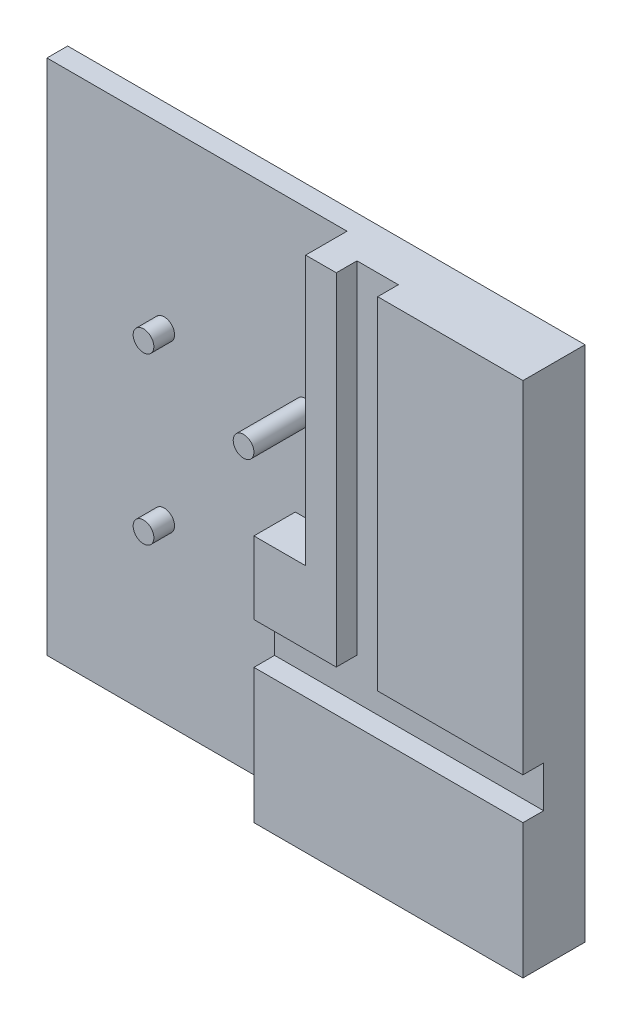
SolidWorks part; units mm, degrees
material "普通碳钢"
ref_plane "前视基准面" through (0, 0, 0) normal (0, 0, 1) x (1, 0, 0)
ref_plane "上视基准面" through (0, 0, 0) normal (0, 1, 0) x (1, 0, 0)
ref_plane "右视基准面" through (0, 0, 0) normal (1, 0, 0) x (0, 0, -1)
sketch "草图1" plane through (0, 0, 0) normal (0, 0, 1) x (1, 0, 0)
  line L1 (-125, 125) -> (125, 125)
  line L2 (-125, 125) -> (-125, -125)
  line L3 (-125, -125) -> (125, -125)
  line L4 (125, 125) -> (125, -125)
  line L5 (0, -125) -> (0, 125) construction
  line L6 (-125, 0) -> (125, 0) construction
  point P0 (0, 0)
  dimension "D1" = 250
  dimension "D2" = 250
extrude "凸台-拉伸1" add sketch "草图1" against normal blind 10
sketch "草图2" plane through (0, 0, 0) normal (0, 0, 1) x (1, 0, 0)
  line L0 (-79.1874, 0) -> (75.0286, 0) construction
  line L2 (-68.35, -38.3641) -> (-68.35, 40) construction
  circle A0 centre (-68.35, 40) radius 5
  dimension "D3" = 10
  dimension "D1" = 68.35
  dimension "D2" = 40
extrude "凸台-拉伸2" add sketch "草图2" along normal blind 10
mirror "镜向1" about plane through (0, 0, 0) normal (0, 1, 0) of "凸台-拉伸2"
sketch "草图3" plane through (0, 0, 0) normal (0, 0, 1) x (1, 0, 0)
  line L0 (-68.35, 40) -> (0, 40) construction
  circle A0 centre (0, 40) radius 5
  dimension "D2" = 10
  dimension "D1" = 68.35
extrude "凸台-拉伸3" add sketch "草图3" along normal blind 30
sketch "草图4" plane through (0, 0, 0) normal (0, 0, 1) x (1, 0, 0)
  line L0 (125, 125) -> (-125, 125) construction
  line L1 (-68.35, -40) -> (51.3009, -40) construction
  line L2 (34.8, 125) -> (20, 125)
  line L3 (34.8, 125) -> (34.8, -40)
  line L4 (34.8, -40) -> (20, -40)
  line L5 (20, 125) -> (20, -40)
  circle A0 centre (0, 40) radius 5 construction
  dimension "D1" = 34.8
  dimension "D2" = 0
  dimension "D3" = 14.8
extrude "凸台-拉伸4" add sketch "草图4" along normal blind 20
sketch "草图5" plane through (0, 0, 0) normal (0, 0, 1) x (1, 0, 0)
  line L0 (125, -125) -> (125, 125) construction
  line L1 (25, -60) -> (125, -60)
  line L2 (25, -60) -> (25, -125)
  line L3 (25, -125) -> (125, -125)
  line L4 (125, -60) -> (125, -125)
  line L5 (-125, -125) -> (125, -125) construction
  line L6 (20, -40) -> (34.8, -40) construction
  dimension "D1" = 100
  dimension "D2" = 20
extrude "凸台-拉伸5" add sketch "草图5" along normal blind 20
sketch "草图6" plane through (0, 0, 0) normal (0, 0, 1) x (1, 0, 0)
  line L0 (125, -60) -> (125, 125) construction
  line L1 (25, -125) -> (125, -125)
  line L2 (25, -125) -> (25, 125)
  line L3 (25, 125) -> (125, 125)
  line L4 (125, -125) -> (125, 125)
  line L5 (125, 125) -> (34.8, 125) construction
extrude "凸台-拉伸6" add sketch "草图6" along normal blind 10
sketch "草图7" plane through (0, 0, 10) normal (0, 0, 1) x (1, 0, 0)
  line L0 (125, 125) -> (34.8, 125) construction
  line L1 (54.8, 125) -> (125, 125)
  line L2 (54.8, 125) -> (54.8, -40)
  line L3 (54.8, -40) -> (125, -40)
  line L4 (125, 125) -> (125, -40)
  line L5 (125, -60) -> (125, 125) construction
  line L6 (34.8, 125) -> (34.8, -40) construction
  circle A0 centre (-68.35, -40) radius 5 construction
  dimension "D1" = 20
  dimension "D2" = 0
extrude "凸台-拉伸7" add sketch "草图7" along normal blind 10
sketch "草图8" plane through (0, 0, 0) normal (0, 0, 1) x (1, 0, 0)
  line L1 (25, -125) -> (-5, -125)
  line L2 (25, -125) -> (25, -5)
  line L3 (25, -5) -> (-5, -5)
  line L4 (-5, -125) -> (-5, -5)
  dimension "D1" = 30
  dimension "D2" = 120
extrude "凸台-拉伸8" add sketch "草图8" along normal blind 20
sketch "草图9" plane through (0, 0, 20) normal (0, 0, 1) x (1, 0, 0)
  line L0 (-5, -5) -> (-5, -125) construction
  line L1 (25, -60) -> (-5, -60)
  line L2 (25, -60) -> (25, -40)
  line L3 (25, -40) -> (-5, -40)
  line L4 (-5, -60) -> (-5, -40)
  line L5 (25, -40) -> (34.8, -40) construction
extrude "切除-拉伸1" cut sketch "草图9" against normal blind 10
